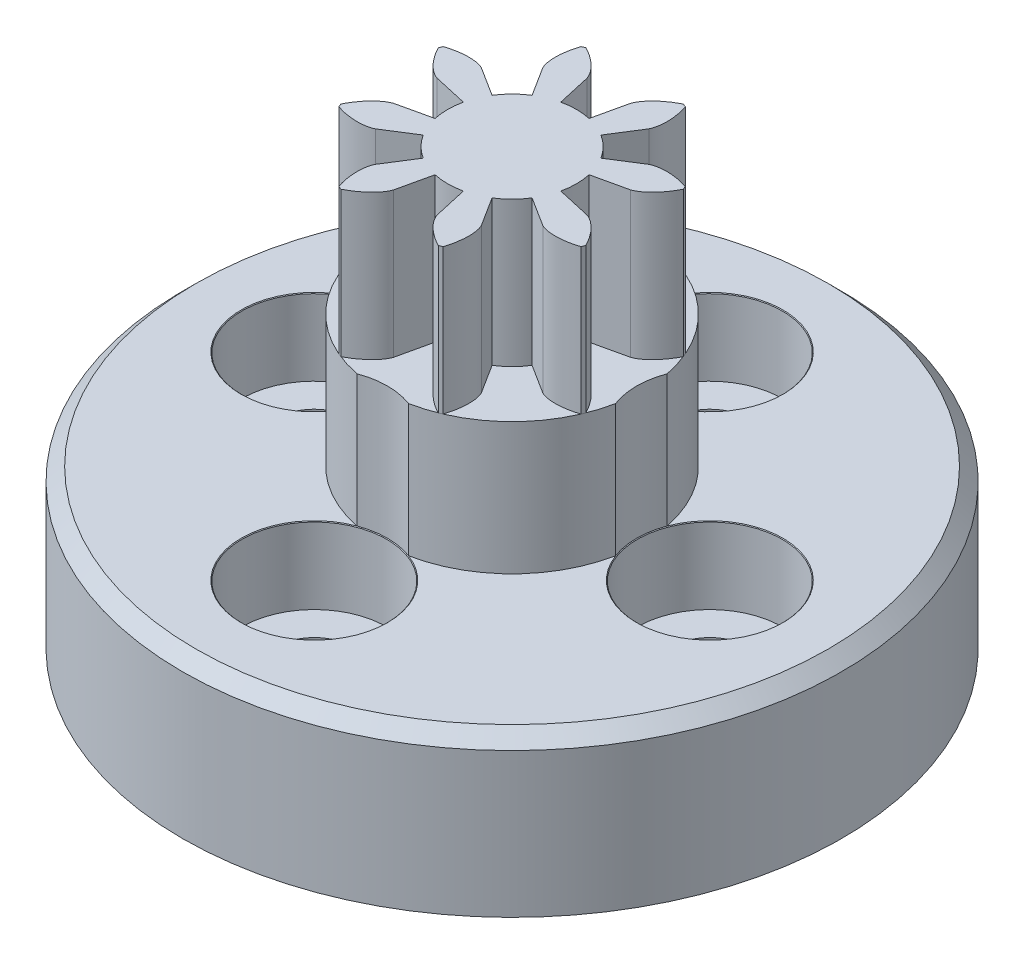
SolidWorks part; units mm, degrees
ref_plane "Front Plane" through (0, 0, 0) normal (0, 0, 1) x (1, 0, 0)
ref_plane "Top Plane" through (0, 0, 0) normal (0, 1, 0) x (1, 0, 0)
ref_plane "Right Plane" through (0, 0, 0) normal (1, 0, 0) x (0, 0, -1)
sketch "Sketch1" plane through (0, 0, 0) normal (0, 1, 0) x (1, 0, 0)
  circle A0 centre (0, 0) radius 12.5
  dimension "D1" = 25
extrude "Boss-Extrude1" add sketch "Sketch1" along normal blind 5.98
hole_wizard "CBORE for M2.5 Hex Socket Head Cap Screw1" positions "Sketch2" profile "Sketch3" counterbore size "M2.5" standard "DIN" end condition through all
sketch "Sketch2" plane through (0, 5.98, 0) normal (0, 1, 0) x (1, 0, 0)
  circle A0 centre (0, 0) radius 7.5
  point P5 (0, 7.5)
  point P7 (7.5, 0)
  point P9 (0, -7.5)
  point P11 (-7.5, 0)
  dimension "D1" = 15
sketch "Sketch3" plane through (-7.5, 5.98, 0) normal (1, 0, 0) x (0, 0, 1)
  line L0 (0, 0) -> (0, 5.98)
  line L1 (0, 5.98) -> (1.45, 5.98)
  line L3 (1.45, 5.98) -> (1.45, 2.9)
  line L4 (2.75, 2.9) -> (1.45, 2.9)
  line L5 (2.75, 2.9) -> (2.75, 0.025)
  line L6 (2.75, 0.025) -> (2.775, 0)
  line L7 (2.775, 0) -> (0, 0)
  line L8 (-2.75, 0.025) -> (-2.775, 0) construction
  line L11 (0, -6.35) -> (0, 107.95) construction
  dimension "Thru Hole Dia." = 2.9
  dimension "Thru Hole Depth" = 5.98
  dimension "C'Bore Dia." = 5.5
  dimension "C'Bore Depth" = 2.9
  dimension "Near C'Sink Dia." = 5.55
  dimension "Near C'Sink Angle" = 90
sketch "Sketch5" plane through (0, 5.98, 0) normal (0, 1, 0) x (1, 0, 0)
  circle A0 centre (0, 0) radius 5
  circle A1 centre (0, 7.5) radius 2.775
  circle A2 centre (7.5, 0) radius 2.775
  circle A3 centre (0, -7.5) radius 2.775
  circle A4 centre (-7.5, 0) radius 2.775
  circle M3 centre (0, 7.5) radius 2.775
  circle M4 centre (7.5, 0) radius 2.775
  circle M5 centre (0, -7.5) radius 2.775
  circle M6 centre (-7.5, 0) radius 2.775
  dimension "D1" = 10
extrude "Boss-Extrude2" add sketch "Sketch5" along normal blind 5 contours A0 M5 M4 M3 M6
sketch "Sketch4" plane through (0, 10.98, 0) normal (0, 1, 0) x (1, 0, 0)
  line L0 (-0.5364, 2.3836) -> (-0.8252, 3.6671)
  line L1 (-2.0095, 3.1765) -> (-1.3062, 2.0647)
  line L2 (-1.3062, 2.0647) -> (-0.5364, 2.3836)
  line L3 (1.3062, 2.0647) -> (2.0095, 3.1765)
  line L4 (0.8252, 3.6671) -> (0.5364, 2.3836)
  line L5 (0.5364, 2.3836) -> (1.3062, 2.0647)
  line L6 (2.3836, 0.5364) -> (3.6671, 0.8252)
  line L7 (3.1765, 2.0095) -> (2.0647, 1.3062)
  line L8 (2.0647, 1.3062) -> (2.3836, 0.5364)
  line L9 (2.0647, -1.3062) -> (3.1765, -2.0095)
  line L10 (3.6671, -0.8252) -> (2.3836, -0.5364)
  line L11 (2.3836, -0.5364) -> (2.0647, -1.3062)
  line L12 (0.5364, -2.3836) -> (0.8252, -3.6671)
  line L13 (2.0095, -3.1765) -> (1.3062, -2.0647)
  line L14 (1.3062, -2.0647) -> (0.5364, -2.3836)
  line L15 (-1.3062, -2.0647) -> (-2.0095, -3.1765)
  line L16 (-0.8252, -3.6671) -> (-0.5364, -2.3836)
  line L17 (-0.5364, -2.3836) -> (-1.3062, -2.0647)
  line L18 (-2.3836, -0.5364) -> (-3.6671, -0.8252)
  line L19 (-3.1765, -2.0095) -> (-2.0647, -1.3062)
  line L20 (-2.0647, -1.3062) -> (-2.3836, -0.5364)
  line L21 (-2.0647, 1.3062) -> (-3.1765, 2.0095)
  line L22 (-3.6671, 0.8252) -> (-2.3836, 0.5364)
  line L23 (-2.3836, 0.5364) -> (-2.0647, 1.3062)
  arc A0 (-1.8475, 4.6461) -> (-1.9789, 4.5917) centre (0, 0) ccw
  arc A1 (1.9789, 4.5917) -> (1.8475, 4.6461) centre (0, 0) ccw
  arc A2 (4.6461, 1.8475) -> (4.5917, 1.9789) centre (0, 0) ccw
  arc A3 (4.5917, -1.9789) -> (4.6461, -1.8475) centre (0, 0) ccw
  arc A4 (1.8475, -4.6461) -> (1.9789, -4.5917) centre (0, 0) ccw
  arc A5 (-1.9789, -4.5917) -> (-1.8475, -4.6461) centre (0, 0) ccw
  arc A6 (-4.6461, -1.8475) -> (-4.5917, -1.9789) centre (0, 0) ccw
  arc A7 (-4.5917, 1.9789) -> (-4.6461, 1.8475) centre (0, 0) ccw
  arc A8 (-1.3062, 2.0647) -> (-2.0647, 1.3062) centre (0, 0) ccw
  arc A9 (0.5364, 2.3836) -> (-0.5364, 2.3836) centre (0, 0) ccw
  arc A10 (2.0647, 1.3062) -> (1.3062, 2.0647) centre (0, 0) ccw
  arc A11 (2.3836, -0.5364) -> (2.3836, 0.5364) centre (0, 0) ccw
  arc A12 (1.3062, -2.0647) -> (2.0647, -1.3062) centre (0, 0) ccw
  arc A13 (-0.5364, -2.3836) -> (0.5364, -2.3836) centre (0, 0) ccw
  arc A14 (-2.0647, -1.3062) -> (-1.3062, -2.0647) centre (0, 0) ccw
  arc A15 (-2.3836, 0.5364) -> (-2.3836, -0.5364) centre (0, 0) ccw
  ellipse E0 centre (-1.973, 4.01) end of major axis (-0.8382, 3.3262) minor radius 0.6183 (-0.8252, 3.6671) -> (-1.8475, 4.6461) ccw
  ellipse E1 centre (-1.4947, 4.1991) end of major axis (-1.214, 5.4352) minor radius 0.5729 (-1.9789, 4.5917) -> (-2.0095, 3.1765) ccw
  ellipse E2 centre (1.4403, 4.2306) end of major axis (1.7593, 2.9447) minor radius 0.6183 (2.0095, 3.1765) -> (1.9789, 4.5917) ccw
  ellipse E3 centre (1.9123, 4.0261) end of major axis (2.9848, 4.7017) minor radius 0.5729 (1.8475, 4.6461) -> (0.8252, 3.6671) ccw
  ellipse E4 centre (4.01, 1.973) end of major axis (3.3262, 0.8382) minor radius 0.6183 (3.6671, 0.8252) -> (4.6461, 1.8475) ccw
  ellipse E5 centre (4.1991, 1.4947) end of major axis (5.4352, 1.214) minor radius 0.5729 (4.5917, 1.9789) -> (3.1765, 2.0095) ccw
  ellipse E6 centre (4.2306, -1.4403) end of major axis (2.9447, -1.7593) minor radius 0.6183 (3.1765, -2.0095) -> (4.5917, -1.9789) ccw
  ellipse E7 centre (4.0261, -1.9123) end of major axis (3.3505, -0.8398) minor radius 0.5729 (4.6461, -1.8475) -> (3.6671, -0.8252) ccw
  ellipse E8 centre (1.973, -4.01) end of major axis (3.1079, -4.6937) minor radius 0.6183 (0.8252, -3.6671) -> (1.8475, -4.6461) ccw
  ellipse E9 centre (1.4947, -4.1991) end of major axis (1.7753, -2.963) minor radius 0.5729 (1.9789, -4.5917) -> (2.0095, -3.1765) ccw
  ellipse E10 centre (-1.4403, -4.2306) end of major axis (-1.1214, -5.5166) minor radius 0.6183 (-2.0095, -3.1765) -> (-1.9789, -4.5917) ccw
  ellipse E11 centre (-1.9123, -4.0261) end of major axis (-0.8398, -3.3505) minor radius 0.5729 (-1.8475, -4.6461) -> (-0.8252, -3.6671) ccw
  ellipse E12 centre (-4.01, -1.973) end of major axis (-3.3262, -0.8382) minor radius 0.6183 (-3.6671, -0.8252) -> (-4.6461, -1.8475) ccw
  ellipse E13 centre (-4.1991, -1.4947) end of major axis (-2.963, -1.7753) minor radius 0.5729 (-4.5917, -1.9789) -> (-3.1765, -2.0095) ccw
  ellipse E14 centre (-4.2306, 1.4403) end of major axis (-2.9447, 1.7593) minor radius 0.6183 (-3.1765, 2.0095) -> (-4.5917, 1.9789) ccw
  ellipse E15 centre (-4.0261, 1.9123) end of major axis (-3.3505, 0.8398) minor radius 0.5729 (-4.6461, 1.8475) -> (-3.6671, 0.8252) ccw
  point P2 (-0.3599, 4.4614)
  point P3 (0.1376, 4.8286)
  point P4 (0.4269, 3.3954)
  point P5 (0.5693, 3.7053)
  point P6 (-0.0005, 5.0011)
  point P7 (0.3973, 4.3999)
  point P8 (-1.1171, 4.5229)
  point P17 (0.1544, 4.453)
  point P18 (0.622, 4.1221)
  point P19 (-0.5779, 3.4184)
  point P20 (-0.1427, 5.0011)
  point P21 (-0.7125, 3.7053)
  point P22 (-0.5405, 4.3999)
  point P23 (0.8493, 4.5062)
  point P146 (0, 0)
  point P147 (0, 0)
extrude "Boss-Extrude3" add sketch "Sketch4" along normal blind 5.5 separate body
chamfer "0,5mm Chamfer" distance 0.5 angle 45 1 edges at (0, 5.98, 12.5)
